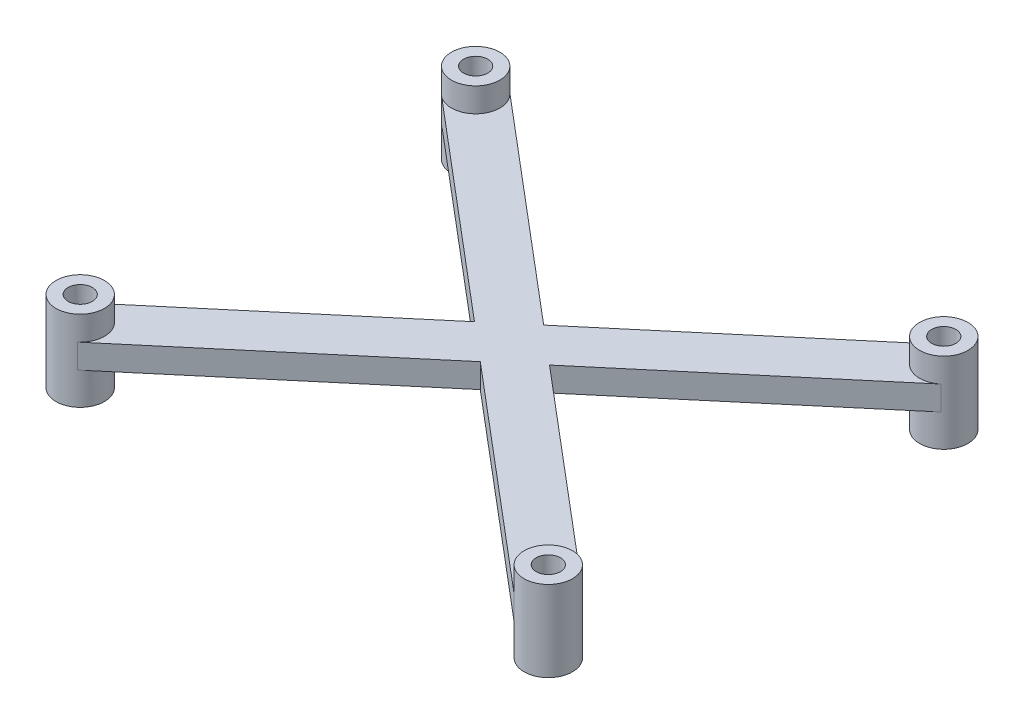
SolidWorks part; units mm, degrees
ref_plane "Alzado" through (0, 0, 0) normal (0, 0, 1) x (1, 0, 0)
ref_plane "Planta" through (0, 0, 0) normal (0, 1, 0) x (1, 0, 0)
ref_plane "Vista lateral" through (0, 0, 0) normal (1, 0, 0) x (0, 0, -1)
sketch "Croquis1" plane through (0, 0, 0) normal (0, 1, 0) x (1, 0, 0)
  line L0 (0, 0) -> (29, 0)
  line L1 (29, 0) -> (29, 24.5)
  line L2 (29, 24.5) -> (-29, 24.5)
  line L3 (-29, 24.5) -> (-29, -24.5)
  line L4 (29, 0) -> (29, -24.5)
  circle A0 centre (-29, 24.5) radius 3
  circle A1 centre (-29, -24.5) radius 3
  circle A2 centre (29, -24.5) radius 3
  circle A3 centre (29, 24.5) radius 3
  dimension "D5" = 6
  dimension "D6" = 6
  dimension "D7" = 6
  dimension "D8" = 6
  dimension "D1" = 29
  dimension "D2" = 24.5
  dimension "D3" = 58
  dimension "D4" = 49
extrude "Saliente-Extruir1" add sketch "Croquis1" against normal blind 4 contours A0 | A1 | A2 | A3
sketch "Croquis2" plane through (0, 0, 0) normal (0, 1, 0) x (1, 0, 0)
  line L0 (-27.0639, 26.7917) -> (30.9361, -22.2083)
  line L1 (-30.9361, 22.2083) -> (27.0639, -26.7917)
  line L2 (27.0639, 26.7917) -> (-30.9361, -22.2083)
  line L3 (30.9361, 22.2083) -> (-27.0639, -26.7917)
  circle A0 centre (-29, 24.5) radius 3 construction
  circle A1 centre (29, -24.5) radius 3 construction
  circle A2 centre (29, 24.5) radius 3 construction
  circle A3 centre (-29, -24.5) radius 3 construction
  circle A4 centre (-29, 24.5) radius 3
  circle A5 centre (-29, -24.5) radius 3
  circle A6 centre (29, -24.5) radius 3
  circle A7 centre (29, 24.5) radius 3
  circle M9 centre (-29, 24.5) radius 3
extrude "Saliente-Extruir2" add sketch "Croquis2" along normal blind 3 contours A5 L3 L1 L2 | L3 L0 L2 L1 | A7 L2 L0 L3 | L2 L0 L1 M9 | A6 L0 L3 L1 | A4
sketch "Croquis3" plane through (0, 3, 0) normal (0, 1, 0) x (1, 0, 0)
  circle A0 centre (-29, 24.5) radius 3
  circle A1 centre (-29, -24.5) radius 3
  circle A2 centre (29, -24.5) radius 3
  circle A3 centre (29, 24.5) radius 3
extrude "Saliente-Extruir3" add sketch "Croquis3" along normal blind 3
sketch "Croquis5" plane through (0, 6, 0) normal (0, 1, 0) x (1, 0, 0)
  circle A0 centre (-29, 24.5) radius 1.5
  circle A1 centre (29, 24.5) radius 1.5
  circle A2 centre (29, -24.5) radius 1.5
  circle A3 centre (-29, -24.5) radius 1.5
  dimension "D1" = 3
  dimension "D2" = 3
  dimension "D3" = 3
  dimension "D4" = 3
extrude "Cortar-Extruir1" cut sketch "Croquis5" against normal blind 13
